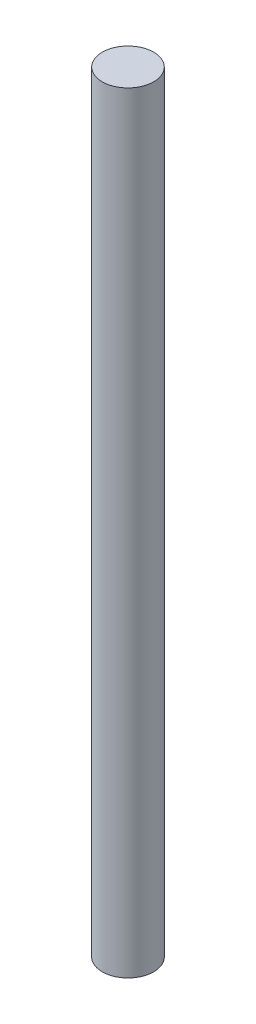
SolidWorks part; units mm, degrees
ref_plane "Front" through (0, 0, 0) normal (0, 0, 1) x (1, 0, 0)
ref_plane "Top" through (0, 0, 0) normal (0, 1, 0) x (1, 0, 0)
ref_plane "Right" through (0, 0, 0) normal (1, 0, 0) x (0, 0, -1)
sketch "Sketch1" plane through (0, 0, 0) normal (0, 1, 0) x (1, 0, 0)
  circle A0 centre (0, 0) radius 1
  dimension "D1" = 2
extrude "Boss-Extrude1" add sketch "Sketch1" along normal blind 30
